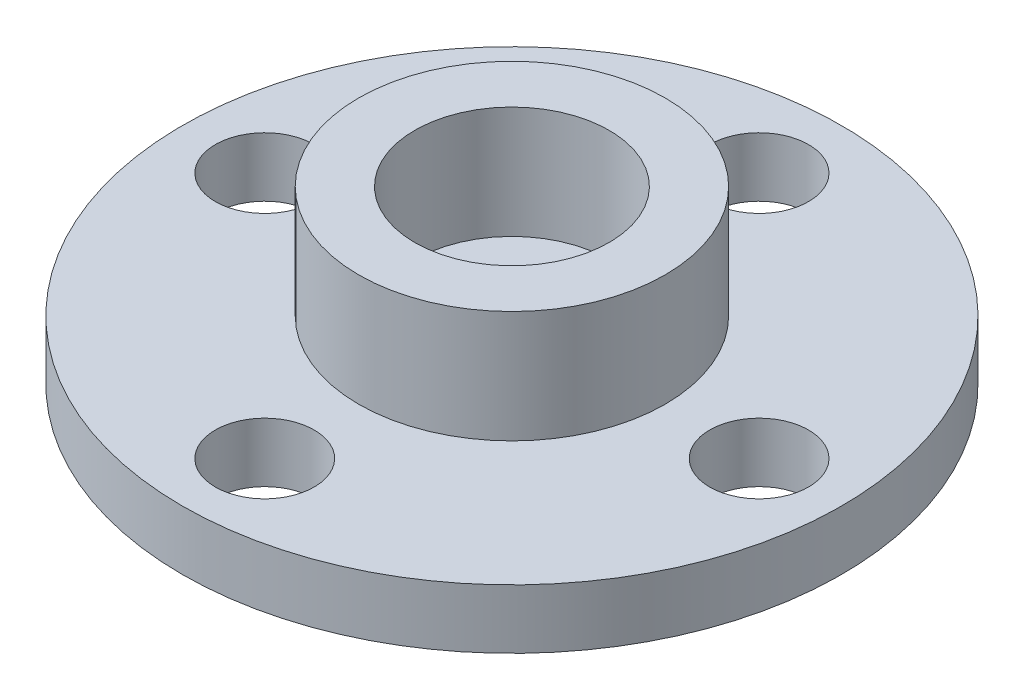
SolidWorks part; units mm, degrees
material "1060 Alloy"
ref_plane "Front Plane" through (0, 0, 0) normal (0, 0, 1) x (1, 0, 0)
ref_plane "Top Plane" through (0, 0, 0) normal (0, 1, 0) x (1, 0, 0)
ref_plane "Right Plane" through (0, 0, 0) normal (1, 0, 0) x (0, 0, -1)
sketch "Sketch1" plane through (0, 0, 0) normal (0, 1, 0) x (1, 0, 0)
  circle A0 centre (0, 0) radius 10
  dimension "D1" = 20
extrude "Boss-Extrude1" add sketch "Sketch1" along normal blind 5.2
sketch "Sketch2" plane through (0, 5.2, 0) normal (0, 1, 0) x (1, 0, 0)
  circle A0 centre (0, 0) radius 10
  circle A1 centre (0, 0) radius 4.65
  dimension "D1" = 9.3
extrude "Cut-Extrude1" cut sketch "Sketch2" against normal blind 3.4
sketch "Sketch3" plane through (0, 1.8, 0) normal (0, 1, 0) x (1, 0, 0)
  circle A0 centre (0, 0) radius 1.5
  circle A1 centre (0, 0) radius 7.5 construction
  circle A2 centre (-7.5, 0) radius 1.5
  circle A3 centre (0, 7.5) radius 1.5
  circle A4 centre (7.5, 0) radius 1.5
  circle A5 centre (0, -7.5) radius 1.5
  point P15 (0, 0)
  dimension "D1" = 3
  dimension "D2" = 15
  dimension "D3" = 3
  dimension "D4" = 4
extrude "Cut-Extrude2" cut sketch "Sketch3" against normal up to next
sketch "Sketch4" plane through (0, 5.2, 0) normal (0, 1, 0) x (1, 0, 0)
  circle A0 centre (0, 0) radius 2.95
  dimension "D1" = 5.9
extrude "Cut-Extrude3" cut sketch "Sketch4" against normal up to surface (3.4 mm away) up to face at (0, 1.8, 9)
